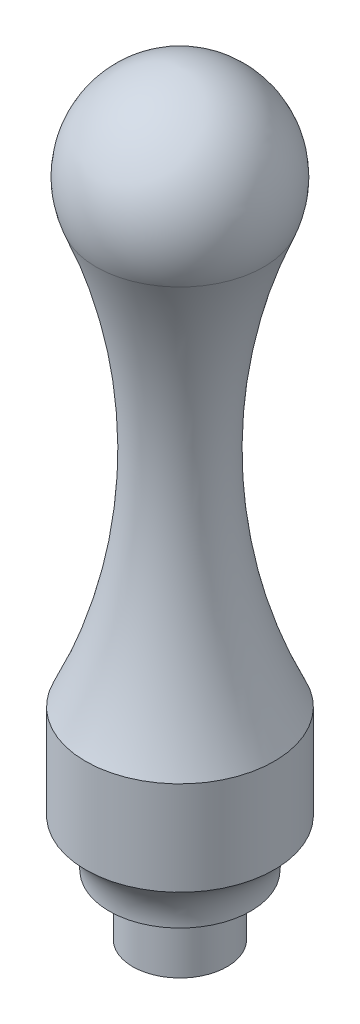
SolidWorks part; units mm, degrees
ref_plane "Front" through (0, 0, 0) normal (0, 0, 1) x (1, 0, 0)
ref_plane "Top" through (0, 0, 0) normal (0, 1, 0) x (-1, 0, 0)
ref_plane "Right" through (0, 0, 0) normal (1, 0, 0) x (0, 0, -1)
sketch "Sketch1" plane through (0, 0, 0) normal (0, 0, 1) x (1, 0, 0)
  line L0 (0, 0) -> (0, -26.0844) construction
  line L1 (0, 0) -> (5, 0)
  line L2 (5, 0) -> (5, 6.35)
  line L3 (5, 6.35) -> (7.5, 6.35)
  line L4 (10, 11.3998) -> (10, 21.35)
  line L5 (0, 80) -> (0, 0)
  line L6 (0, 0) -> (0, -6.286) construction
  arc A0 (7.5, 6.35) -> (10, 11.3998) centre (13.85, 6.35) cw
  arc A1 (10, 21.35) -> (8.8884, 66.1588) centre (59.6556, 45) cw
  arc A2 (0, 80) -> (8.8884, 66.1588) centre (-0.342, 70.0058) cw
  dimension "D5" = 10
  dimension "D6" = 21.35
  dimension "D3" = 6.35
  dimension "D8" = 55
  dimension "D10" = 10
  dimension "D1" = 80
  dimension "D2" = 6.35
  dimension "D4" = 7.5
  dimension "D7" = 10
  dimension "D9" = 45
revolve "Base-Revolve" add sketch "Sketch1" angle 360 about L0
